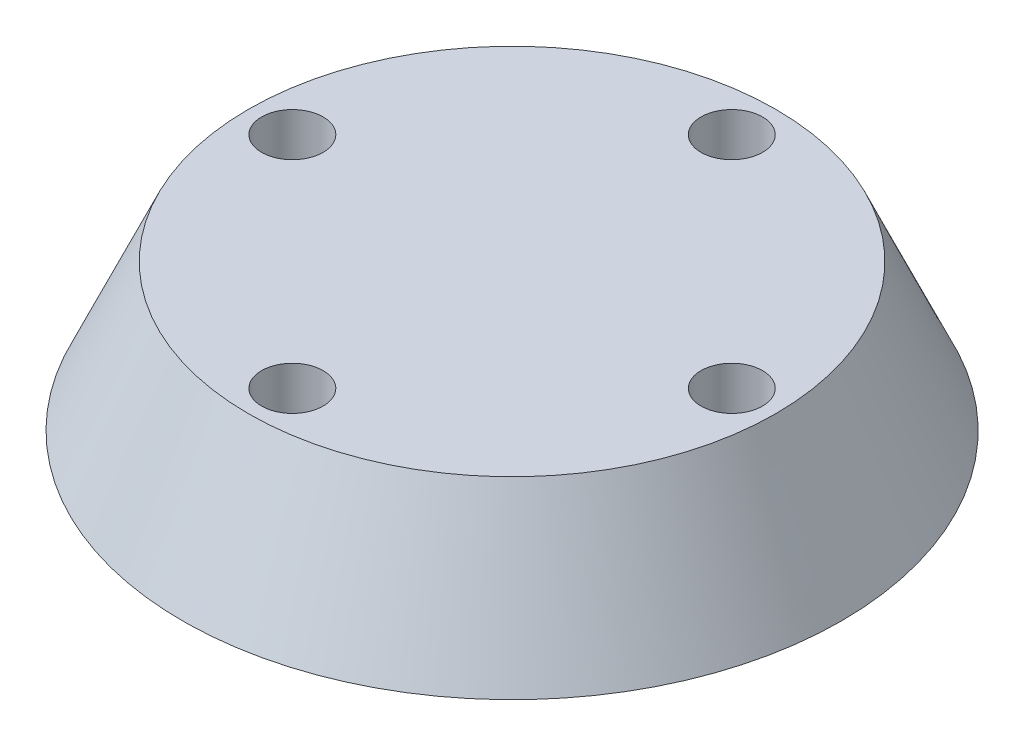
SolidWorks part; units mm, degrees
ref_plane "前视基准面" through (0, 0, 0) normal (0, 0, 1) x (1, 0, 0)
ref_plane "上视基准面" through (0, 0, 0) normal (0, 1, 0) x (1, 0, 0)
ref_plane "右视基准面" through (0, 0, 0) normal (1, 0, 0) x (0, 0, -1)
other "Configuration Table"
sketch "草图2" plane through (0, 0, 0) normal (0, 1, 0) x (1, 0, 0)
  line L0 (0, 0) -> (0, 9.5)
  line L1 (0, 0) -> (0, -9.5)
  line L2 (0, 0) -> (-8, 0)
  line L3 (0, 0) -> (8, 0)
  circle A0 centre (0, 0) radius 18
ref_plane "基准面4" through (0, -10, 0) normal (0, 1, 0) x (1, 0, 0)
sketch "草图4" plane through (0, -10, 0) normal (0, 1, 0) x (1, 0, 0)
  circle A0 centre (0, 0) radius 22.5
ref_plane "基准面6" through (0, 0, 0) normal (0, 0, -1) x (-1, 0, 0)
sketch "草图8" plane through (0, 0, 0) normal (0, 0, -1) x (-1, 0, 0)
  line L0 (0, 0) -> (-18, 0)
  line L1 (18, 0) -> (-18, 0) construction
  line L2 (-18, 0) -> (-22.5, -10)
  line L3 (22.5, -10) -> (-22.5, -10) construction
  line L4 (-22.5, -10) -> (0, -10)
  line L5 (0, -10) -> (0, 0)
revolve "旋转1" add sketch "草图8" angle 360 about L5
sketch "草图26" plane through (0, -10, 0) normal (0, 1, 0) x (1, 0, 0)
  line L0 (0, 0) -> (0, 18)
  line L1 (0, 0) -> (18, 0)
  line L2 (0, 0) -> (0, -18)
  line L3 (0, 0) -> (-18, 0)
  circle A1 centre (0, 0) radius 18 construction
  circle A2 centre (18, 0) radius 2.1
  circle A3 centre (0, -18) radius 2.1
  circle A4 centre (0, 18) radius 2.1
  circle A5 centre (-18, 0) radius 2.1
extrude "切除-拉伸2" cut sketch "草图26" along normal blind 4 contours A3 | A5 | A4 | A2
sketch "草图36" plane through (0, 0, 0) normal (0, 1, 0) x (1, 0, 0)
  circle A0 centre (0, 0) radius 15
  circle A1 centre (0, 15) radius 2.1
  circle A2 centre (15, 0) radius 2.1
  circle A3 centre (0, -15) radius 2.1
  circle A4 centre (-15, 0) radius 2.1
  point P14 (0, 0)
  dimension "D1" = 4
extrude "切除-拉伸3" cut sketch "草图36" against normal blind 4 contours A2 | A3 | A1 | A4
